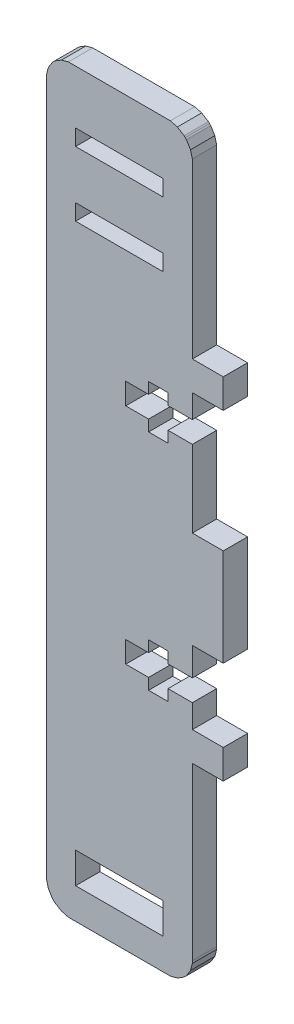
SolidWorks part; units mm, degrees
material "Balsa"
ref_plane "Front Plane" through (0, 0, 0) normal (0, 0, 1) x (1, 0, 0)
ref_plane "Top Plane" through (0, 0, 0) normal (0, 1, 0) x (1, 0, 0)
ref_plane "Right Plane" through (0, 0, 0) normal (1, 0, 0) x (0, 0, -1)
sketch "Sketch1" plane through (0, 0, 0) normal (0, 0, 1) x (1, 0, 0)
  line L0 (-13.1737, -76.1505) -> (6.8262, -76.1505)
  line L1 (-12.1755, -69.8005) -> (5.8255, -69.8005)
  line L2 (-12.1755, -63.4505) -> (5.8255, -63.4505)
  line L3 (11.825, -36.0007) -> (18.175, -36.0007)
  line L4 (11.825, -30.0012) -> (18.175, -30.0012)
  line L5 (6.8262, -27.4993) -> (2.8258, -27.4993)
  line L6 (11.825, -25.1981) -> (6.8262, -25.1981)
  line L7 (2.8258, -25.1981) -> (-1.8758, -25.1981)
  line L8 (11.825, -20.7988) -> (6.8262, -20.7988)
  line L9 (2.8258, -20.7988) -> (-1.8758, -20.7988)
  line L10 (6.8262, -18.5001) -> (2.8258, -18.5001)
  line L11 (11.825, -15) -> (18.175, -15)
  line L12 (11.825, 5) -> (18.175, 5)
  line L13 (6.8262, 18.5001) -> (2.8258, 18.5001)
  line L14 (11.825, 20.7988) -> (6.8262, 20.7988)
  line L15 (2.8258, 20.7988) -> (-1.8758, 20.7988)
  line L16 (11.825, 25.1981) -> (6.8262, 25.1981)
  line L17 (2.8258, 25.1981) -> (-1.8758, 25.1981)
  line L18 (6.8262, 27.4993) -> (2.8258, 27.4993)
  line L19 (11.825, 30.0012) -> (18.175, 30.0012)
  line L20 (11.825, 36.0007) -> (18.175, 36.0007)
  line L21 (6.8262, 76.1505) -> (-13.1737, 76.1505)
  line L22 (-18.175, 71.1492) -> (-18.175, -71.1518)
  line L23 (-12.1755, -63.4505) -> (-12.1755, -69.8005)
  line L24 (-1.8758, 25.1981) -> (-1.8758, 20.7988)
  line L25 (-1.8758, -25.1981) -> (-1.8758, -20.7988)
  line L26 (2.8258, 27.4993) -> (2.8258, 25.1981)
  line L27 (2.8258, 20.7988) -> (2.8258, 18.5001)
  line L28 (2.8258, -27.4993) -> (2.8258, -25.1981)
  line L29 (2.8258, -20.7988) -> (2.8258, -18.5001)
  line L30 (5.8255, -69.8005) -> (5.8255, -63.4505)
  line L31 (6.8262, 27.4993) -> (6.8262, 25.1981)
  line L32 (6.8262, 20.7988) -> (6.8262, 18.5001)
  line L33 (6.8262, -27.4993) -> (6.8262, -25.1981)
  line L34 (6.8262, -20.7988) -> (6.8262, -18.5001)
  line L35 (11.825, -71.1518) -> (11.825, -36.0007)
  line L36 (11.825, -30.0012) -> (11.825, -25.1981)
  line L37 (11.825, -20.7988) -> (11.825, -15)
  line L38 (11.825, 5) -> (11.825, 20.7988)
  line L39 (11.825, 25.1981) -> (11.825, 30.0012)
  line L40 (11.825, 36.0007) -> (11.825, 71.1492)
  line L41 (18.175, 36.0007) -> (18.175, 30.0012)
  line L42 (18.175, 5) -> (18.175, -15)
  line L43 (18.175, -30.0012) -> (18.175, -36.0007)
  line L44 (6.8262, -76.1505) -> (7.3038, -76.1505)
  line L45 (7.3038, -76.1505) -> (8.7389, -75.7695)
  line L46 (8.7389, -75.7695) -> (10.1257, -74.9186)
  line L47 (10.1257, -74.9186) -> (10.3619, -74.6849)
  line L48 (10.3619, -74.6849) -> (10.5981, -74.4512)
  line L49 (10.5981, -74.4512) -> (11.4465, -73.0644)
  line L50 (11.4465, -73.0644) -> (11.8275, -71.6267)
  line L51 (11.8275, -71.6267) -> (11.825, -71.1518)
  line L52 (-18.175, -71.1518) -> (-18.175, -71.6267)
  line L53 (-18.175, -71.6267) -> (-17.794, -73.0644)
  line L54 (-17.794, -73.0644) -> (-16.9456, -74.4512)
  line L55 (-16.9456, -74.4512) -> (-16.7094, -74.6849)
  line L56 (-16.7094, -74.6849) -> (-16.4757, -74.9186)
  line L57 (-16.4757, -74.9186) -> (-15.0889, -75.7695)
  line L58 (-15.0889, -75.7695) -> (-13.6538, -76.1505)
  line L59 (-13.6538, -76.1505) -> (-13.1737, -76.1505)
  line L60 (-13.1737, 76.1505) -> (-13.6538, 76.1505)
  line L61 (-13.6538, 76.1505) -> (-15.0889, 75.7695)
  line L62 (-15.0889, 75.7695) -> (-16.4757, 74.9186)
  line L63 (-16.4757, 74.9186) -> (-16.7094, 74.6874)
  line L64 (-16.7094, 74.6874) -> (-16.9456, 74.4512)
  line L65 (-16.9456, 74.4512) -> (-17.794, 73.0644)
  line L66 (-17.794, 73.0644) -> (-18.175, 71.6267)
  line L67 (-18.175, 71.6267) -> (-18.175, 71.1492)
  line L68 (11.825, 71.1492) -> (11.825, 71.6267)
  line L69 (11.825, 71.6267) -> (11.444, 73.0644)
  line L70 (11.444, 73.0644) -> (10.5956, 74.4512)
  line L71 (10.5956, 74.4512) -> (10.3619, 74.6874)
  line L72 (10.3619, 74.6874) -> (10.1257, 74.9186)
  line L73 (10.1257, 74.9186) -> (8.7389, 75.7695)
  line L74 (8.7389, 75.7695) -> (7.3038, 76.1505)
  line L75 (7.3038, 76.1505) -> (6.8262, 76.1505)
  line L76 (-12.1882, 65.1269) -> (5.8382, 65.1269)
  line L77 (5.8382, 65.1269) -> (5.8382, 61.8249)
  line L78 (5.8382, 61.8249) -> (-12.1882, 61.8249)
  line L79 (-12.1882, 61.8249) -> (-12.1882, 65.1269)
  line L80 (-12.1882, 51.8224) -> (5.8382, 51.8224)
  line L81 (5.8382, 51.8224) -> (5.8382, 48.5254)
  line L82 (5.8382, 48.5254) -> (-12.1882, 48.5254)
  line L83 (-12.1882, 48.5254) -> (-12.1882, 51.8224)
extrude "Boss-Extrude1" add sketch "Sketch1" along normal blind 5
